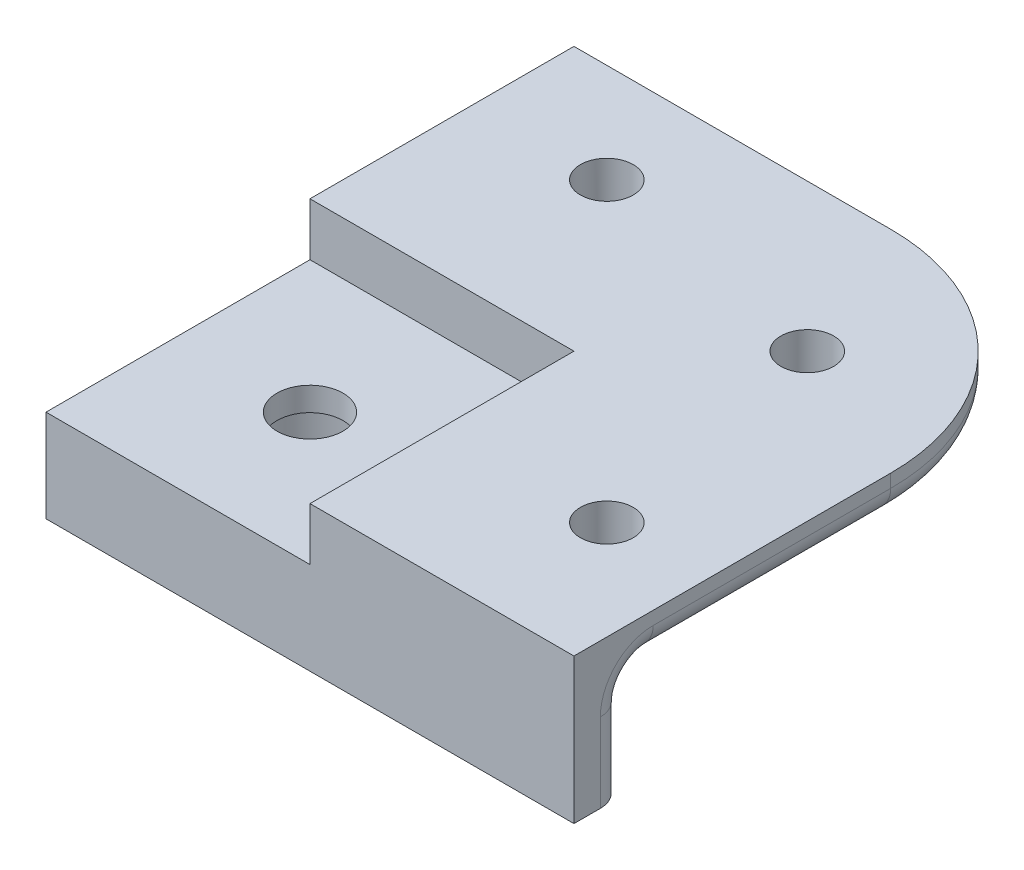
SolidWorks part; units mm, degrees
ref_plane "Front Plane" through (0, 0, 0) normal (0, 0, 1) x (1, 0, 0)
ref_plane "Top Plane" through (0, 0, 0) normal (0, 1, 0) x (1, 0, 0)
ref_plane "Right Plane" through (0, 0, 0) normal (1, 0, 0) x (0, 0, -1)
sketch "Sketch1" plane through (0, 0, 0) normal (0, 1, 0) x (1, 0, 0)
  line L1 (10, -10) -> (-10, -10) construction
  line L2 (10, -10) -> (10, 10)
  line L3 (10, 10) -> (-10, 10)
  line L4 (-10, -10) -> (-10, 10) construction
  line L5 (10, -10) -> (-10, 10) construction
  line L6 (10, 10) -> (-10, -10) construction
  line L7 (10, -10) -> (30, -10)
  line L8 (10, -10) -> (10, -6)
  line L9 (10, -6) -> (30, -6)
  line L10 (30, -10) -> (30, -6)
  line L11 (-10, 10) -> (-6, 10)
  line L12 (-10, 10) -> (-10, 30)
  line L13 (-10, 30) -> (-6, 30)
  line L14 (-6, 10) -> (-6, 30)
  line L15 (-6, 14) -> (14, 14)
  line L16 (-6, 14) -> (-6, 10)
  line L17 (-6, 10) -> (14, 10)
  line L18 (14, 14) -> (14, 10)
  line L19 (14, 10) -> (10, 10)
  line L20 (14, 10) -> (14, -6)
  line L21 (14, -6) -> (10, -6)
  line L22 (10, 10) -> (10, -6)
  point P0 (0, 0)
  dimension "D1" = 20
  dimension "D2" = 20
  dimension "D3" = 4
  dimension "D4" = 4
  dimension "D5" = 4
  dimension "D6" = 4
  dimension "D7" = 20
  dimension "D8" = 20
extrude "Boss-Extrude1" add sketch "Sketch1" along normal blind 11 contours L3 L14 L13 L12 | L18 L15 L14 L3 L17 | L20 L17 L2 L9 | L7 L10 L9 L2
sketch "Sketch2" plane through (0, 0, 0) normal (0, 1, 0) x (1, 0, 0)
  line L1 (-10, -10) -> (10, -10)
  line L2 (-10, -10) -> (-10, 10)
  line L3 (-10, 10) -> (10, 10)
  line L4 (10, -10) -> (10, 10)
  line L5 (-10, -10) -> (10, 10) construction
  line L6 (-10, 10) -> (10, -10) construction
  point P0 (0, 0)
extrude "Boss-Extrude2" add sketch "Sketch2" along normal blind 7
sketch "Sketch3" plane through (0, 11, 0) normal (0, 1, 0) x (1, 0, 0)
  line L1 (-6, 30) -> (14, 30)
  line L2 (-6, 30) -> (-6, 14)
  line L3 (-6, 14) -> (14, 14)
  line L4 (14, 30) -> (14, 14)
  line L5 (30, -6) -> (14, -6)
  line L6 (30, -6) -> (30, 14)
  line L7 (30, 14) -> (14, 14)
  line L8 (14, -6) -> (14, 14)
  arc A0 (30, 14) -> (14, 30) centre (14, 14) ccw
  line M13 (30, -6) -> (14, -6)
  line M14 (14, -6) -> (14, 14)
  line M15 (14, 14) -> (-6, 14)
  line M16 (-6, 14) -> (-6, 30)
extrude "Boss-Extrude3" add sketch "Sketch3" against normal blind 3 contours L4 L1 M16 M15 | L7 A0 L4 | L6 L7 M14 M13
fillet "Fillet1" radius 2 12 edges at (30, 4, 6) (-6, 4, -30) (14, 8, -4) (22, 8, 6) (30, 8, -4) (25.3137, 8, -25.3137) (4, 8, -30) (-6, 8, -22) (4, 8, -14) (-6, 4, -14) (14, 4, -14) (14, 4, 6)
sketch "Sketch4" plane through (0, 0, 0) normal (0, -1, 0) x (1, 0, 0)
  circle A0 centre (0, 0) radius 2.5
  dimension "D1" = 5
extrude "Cut-Extrude1" cut sketch "Sketch4" against normal blind 10
sketch "Sketch5" plane through (0, 0, 0) normal (0, -1, 0) x (1, 0, 0)
  circle A0 centre (0, 0) radius 4.25
  dimension "D1" = 8.5
extrude "Cut-Extrude2" cut sketch "Sketch5" against normal blind 5.2
sketch "Sketch6" plane through (0, 11, 0) normal (0, 1, 0) x (1, 0, 0)
  line L0 (10, -10) -> (22.49, 0) construction
  line L1 (22.49, 0) -> (10, 10) construction
  line L2 (10, 10) -> (25.3137, 25.3137) construction
  circle A0 centre (22.49, 0) radius 2
  arc A1 (30, 14) -> (14, 30) centre (14, 14) ccw construction
  circle A2 centre (0, 22.49) radius 2
  circle A3 centre (18.8388, 18.8388) radius 2
  dimension "D2" = 4
  dimension "D3" = 4
  dimension "D1" = 16
  dimension "D4" = 12.5
extrude "Cut-Extrude3" cut sketch "Sketch6" against normal blind 5.2
